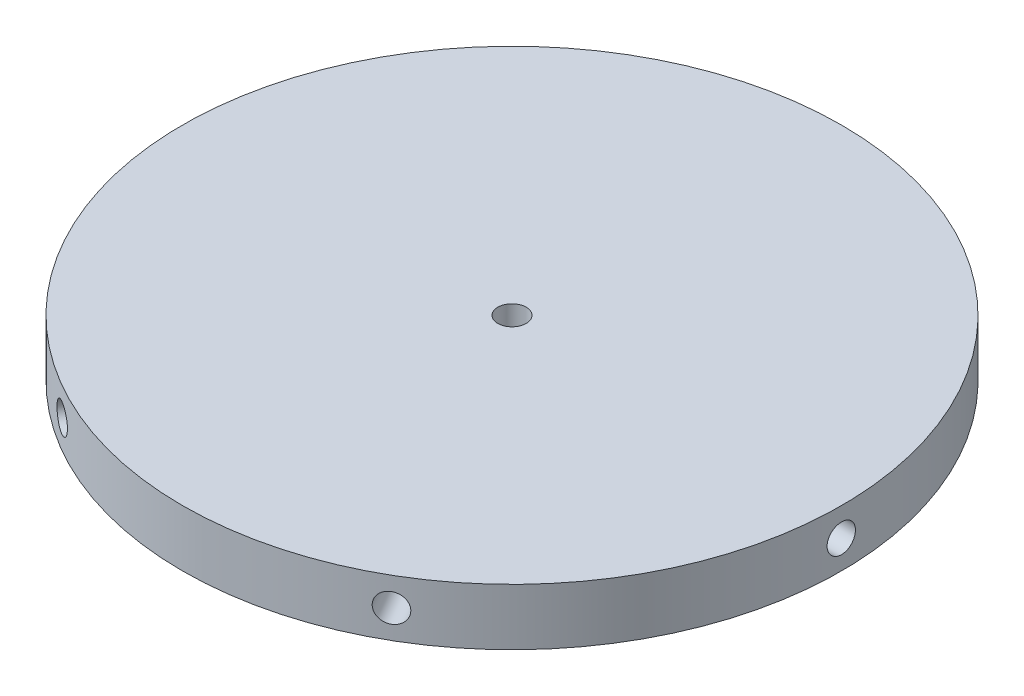
SolidWorks part; units mm, degrees
ref_plane "Front Plane" through (0, 0, 0) normal (0, 0, 1) x (1, 0, 0)
ref_plane "Top Plane" through (0, 0, 0) normal (0, 1, 0) x (1, 0, 0)
ref_plane "Right Plane" through (0, 0, 0) normal (1, 0, 0) x (0, 0, -1)
sketch "Sketch1" plane through (0, 0, 0) normal (0, 1, 0) x (1, 0, 0)
  circle A0 centre (0, 0) radius 73.914
  circle A1 centre (0, 0) radius 3.175
  dimension "D1" = 147.828
  dimension "D2" = 6.35
extrude "Boss-Extrude1" add sketch "Sketch1" along normal blind 12.7
ref_plane "Plane1" through (73.914, 0, 0) normal (1, 0, 0) x (0, 0, -1)
sketch "Sketch2" plane through (73.914, 0, 0) normal (1, 0, 0) x (0, 0, -1)
  line L0 (0, 0) -> (0, 12.7) construction
  line L1 (73.914, 12.7) -> (-73.914, 12.7) construction
  circle A0 centre (0, 6.35) radius 3.175
  dimension "D1" = 6.35
extrude "Cut-Extrude1" cut sketch "Sketch2" against normal blind 12.7
pattern_circular "CirPattern1" count 6 over 360 about axis through (0, 0, 0) along (0, 1, 0) of "Cut-Extrude1"
